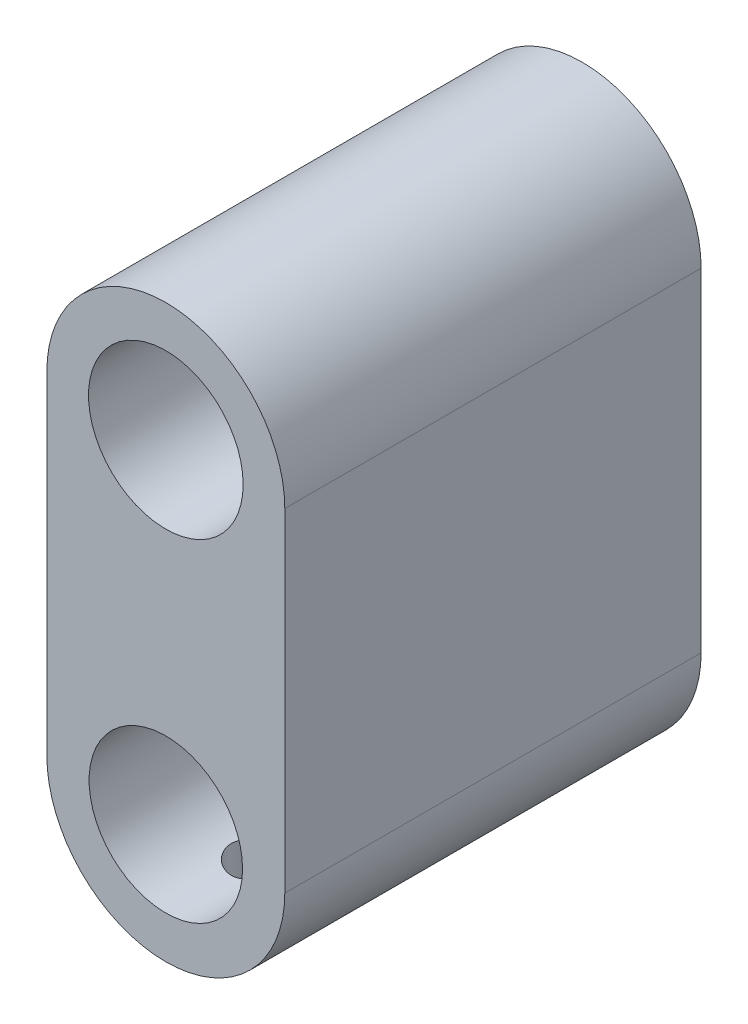
SolidWorks part; units mm, degrees
ref_plane "Alzado" through (0, 0, 0) normal (0, 0, 1) x (1, 0, 0)
ref_plane "Planta" through (0, 0, 0) normal (0, 1, 0) x (1, 0, 0)
ref_plane "Vista lateral" through (0, 0, 0) normal (1, 0, 0) x (0, 0, -1)
sketch "Croquis1" plane through (0, 0, 0) normal (0, 0, 1) x (1, 0, 0)
  line L0 (0, 28) -> (0, 0) construction
  line L1 (10, 28) -> (10, 0)
  line L2 (-10, 28) -> (-10, 0)
  circle A1 centre (0, 0) radius 6.45
  circle A2 centre (0, 28) radius 6.5
  arc A3 (10, 28) -> (-10, 28) centre (0, 28) ccw
  arc A4 (-10, 0) -> (10, 0) centre (0, 0) ccw
  point P2 (0, 14)
  dimension "D1" = 13
  dimension "D2" = 12.9
  dimension "10" = 10
extrude "Saliente-Extruir1" add sketch "Croquis1" along normal blind 35
sketch "Croquis2" plane through (0, 0, 0) normal (0, 1, 0) x (1, 0, 0)
  line L0 (10, 0) -> (-10, 0) construction
  line L1 (-10, -35) -> (10, -35) construction
  circle A0 centre (0, -7.5) radius 2
  circle A1 centre (0, -27.5) radius 2
  dimension "D1" = 7.5
  dimension "4" = 4
  dimension "7.5" = 7.5
extrude "Cortar-Extruir1" cut sketch "Croquis2" against normal blind 10
